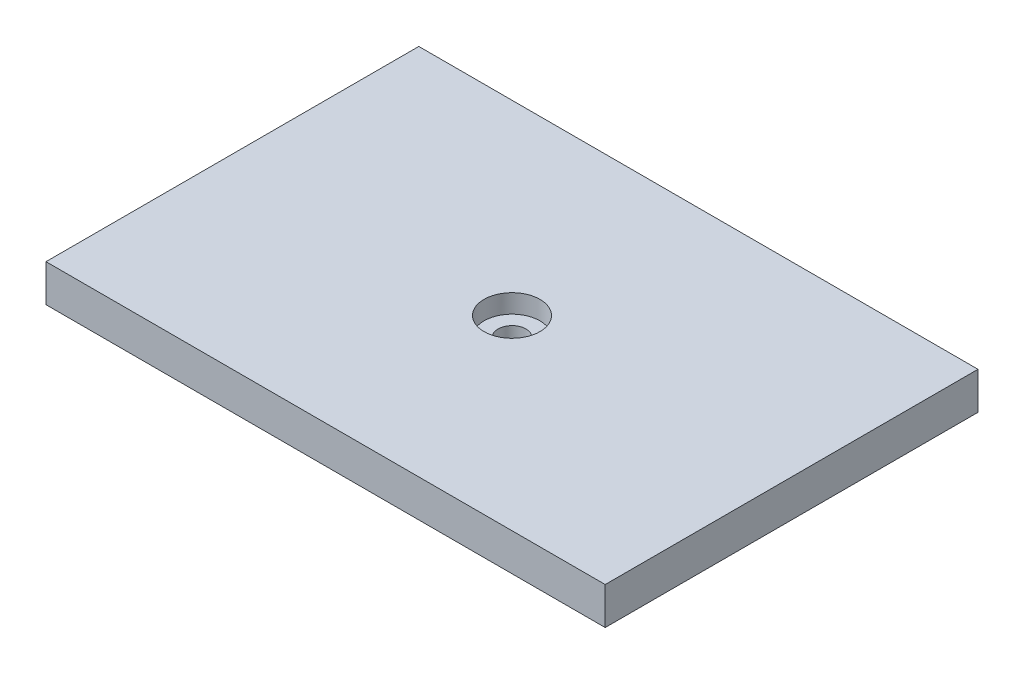
SolidWorks part; units mm, degrees
ref_plane "Front Plane" through (0, 0, 0) normal (0, 0, 1) x (1, 0, 0)
ref_plane "Top Plane" through (0, 0, 0) normal (0, 1, 0) x (1, 0, 0)
ref_plane "Right Plane" through (0, 0, 0) normal (1, 0, 0) x (0, 0, -1)
sketch "Sketch1" plane through (0, 0, 0) normal (0, 1, 0) x (1, 0, 0)
  line L1 (-30, 20) -> (30, 20)
  line L2 (-30, 20) -> (-30, -20)
  line L3 (-30, -20) -> (30, -20)
  line L4 (30, 20) -> (30, -20)
  line L5 (-30, 20) -> (30, -20) construction
  line L6 (-30, -20) -> (30, 20) construction
  point P0 (0, 0)
  dimension "D1" = 60
  dimension "D2" = 40
extrude "Boss-Extrude1" add sketch "Sketch1" along normal blind 4
sketch "Sketch2" plane through (0, 4, 0) normal (0, 1, 0) x (1, 0, 0)
  circle A0 centre (0, 0) radius 3
  dimension "D1" = 6
extrude "Cut-Extrude1" cut sketch "Sketch2" against normal up to surface (4 mm away) up to face at (0, 0, 0)
sketch "Sketch3" plane through (0, 0, 0) normal (0, -1, 0) x (1, 0, 0)
  circle A0 centre (0, 0) radius 1.5
  circle A1 centre (0, 0) radius 3 construction
  circle A2 centre (0, 0) radius 3
  dimension "D1" = 3
extrude "Boss-Extrude2" add sketch "Sketch3" against normal blind 2
